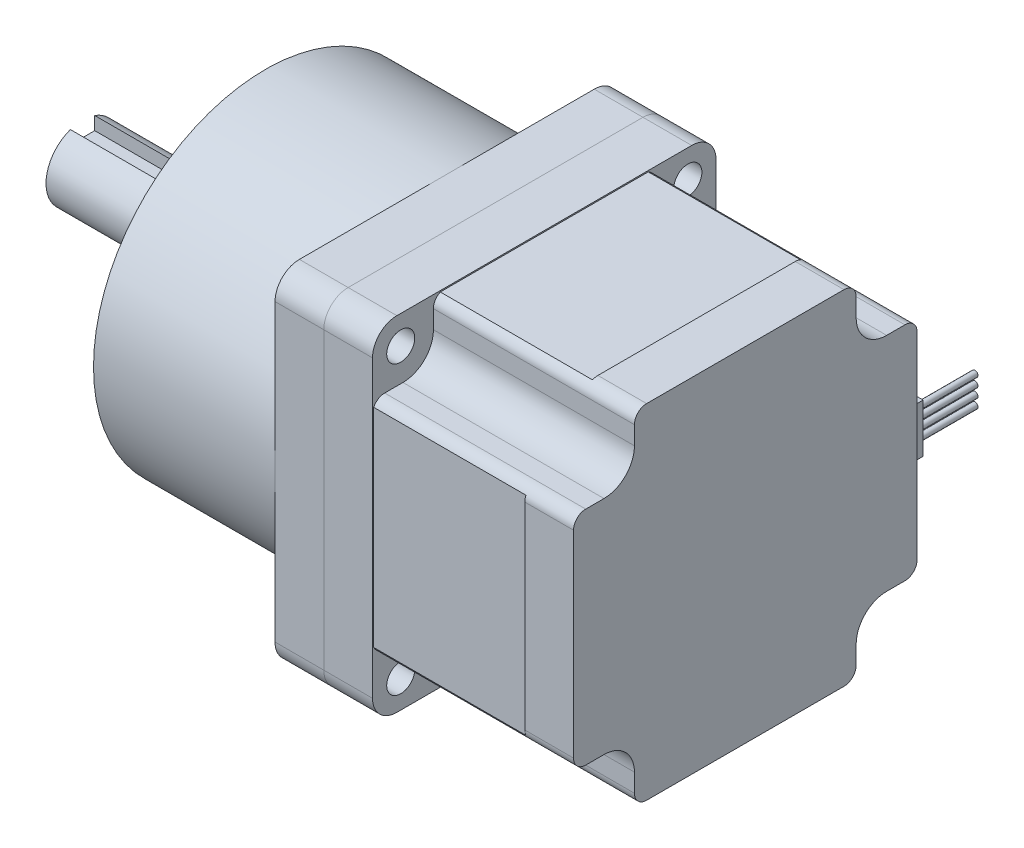
SolidWorks part; units mm, degrees
ref_plane "前视基准面" through (0, 0, 0) normal (0, 0, 1) x (1, 0, 0)
ref_plane "上视基准面" through (0, 0, 0) normal (0, 1, 0) x (1, 0, 0)
ref_plane "右视基准面" through (0, 0, 0) normal (1, 0, 0) x (0, 0, -1)
sketch "草图1" plane through (0, 0, 0) normal (1, 0, 0) x (0, 0, -1)
  line L1 (28.2, -28.2) -> (-28.2, -28.2)
  line L2 (28.2, -28.2) -> (28.2, 28.2)
  line L3 (28.2, 28.2) -> (-28.2, 28.2)
  line L4 (-28.2, -28.2) -> (-28.2, 28.2)
  line L5 (28.2, -28.2) -> (-28.2, 28.2) construction
  line L6 (28.2, 28.2) -> (-28.2, -28.2) construction
  point P0 (0, 0)
  dimension "D1" = 56.4
  dimension "D2" = 56.4
extrude "凸台-拉伸1" add sketch "草图1" along normal mid plane 41
sketch "草图7" plane through (0, 0, 0) normal (1, 0, 0) x (0, 0, -1)
  line L1 (28, 28) -> (-28, 28)
  line L2 (28, 28) -> (28, -28)
  line L3 (28, -28) -> (-28, -28)
  line L4 (-28, 28) -> (-28, -28)
  line L5 (28, 28) -> (-28, -28) construction
  line L6 (28, -28) -> (-28, 28) construction
  line L7 (28.2, -28.2) -> (-28.2, -28.2)
  line L8 (28.2, -28.2) -> (28.2, 28.2)
  line L9 (28.2, 28.2) -> (-28.2, 28.2)
  line L10 (-28.2, -28.2) -> (-28.2, 28.2)
  line L11 (28.2, -28.2) -> (-28.2, 28.2) construction
  line L12 (28.2, 28.2) -> (-28.2, -28.2) construction
  point P0 (0, 0)
  point P6 (0, 0)
  dimension "D1" = 56
  dimension "D2" = 56
  dimension "D3" = 56.4
  dimension "D4" = 56.4
extrude "切除-拉伸1" cut sketch "草图7" against normal mid plane 25
sketch "草图2" plane through (-20.5, 0, 0) normal (-1, 0, 0) x (0, 0, 1)
  circle A0 centre (0, 0) radius 19.05
  dimension "D1" = 38.1
extrude "凸台-拉伸2" add sketch "草图2" along normal blind 1.6
sketch "草图3" plane through (-22.1, 0, 0) normal (-1, 0, 0) x (0, 0, 1)
  circle A0 centre (0, 0) radius 3.175
  dimension "D1" = 6.35
extrude "凸台-拉伸3" add sketch "草图3" along normal blind 19
sketch "草图10" plane through (0, 0, -28.2) normal (0, 0, -1) x (-1, 0, 0)
  line L0 (-20.5, -28.2) -> (-20.5, 28.2) construction
  line L1 (-18.5, -4) -> (-15.5, -4)
  line L2 (-18.5, -4) -> (-18.5, 4)
  line L3 (-18.5, 4) -> (-15.5, 4)
  line L4 (-15.5, -4) -> (-15.5, 4)
  line L5 (-18.5, -4) -> (-15.5, 4) construction
  line L6 (-18.5, 4) -> (-15.5, -4) construction
  point P0 (-17, 0)
  dimension "D1" = 8
  dimension "D2" = 3
  dimension "D3" = 2
  dimension "D4" = 0
extrude "凸台-拉伸4" add sketch "草图10" along normal blind 3
sketch "草图11" plane through (0, 0, -31.2) normal (0, 0, -1) x (-1, 0, 0)
  line L2 (-18.5, -4) -> (-15.5, -4) construction
  line L3 (-18.5, 4) -> (-18.5, -4) construction
  circle A2 centre (-17, -2.5) radius 0.5
  circle A3 centre (-17, -1) radius 0.5
  circle A4 centre (-17, 0.5) radius 0.5
  circle A5 centre (-17, 2) radius 0.5
  point P0 (-17, -4)
  dimension "D2" = 1.5
  dimension "D3" = 1.5
  dimension "D4" = 1
  dimension "D5" = 1
  dimension "D6" = 1
  dimension "D7" = 1
  dimension "D8" = 1.5
  dimension "D9" = 1.5
  dimension "D10" = 1.5
  dimension "D13" = 1.5
  dimension "D14" = 1.5
  dimension "D15" = 1.5
extrude "凸台-拉伸5" add sketch "草图11" along normal blind 10
sketch "草图12" plane through (20.5, 0, 0) normal (1, 0, 0) x (0, 0, -1)
  line L1 (28.2, -28.2) -> (18.2, -28.2)
  line L2 (28.2, -28.2) -> (28.2, -18.2)
  line L3 (28.2, -18.2) -> (18.2, -18.2)
  line L4 (18.2, -28.2) -> (18.2, -18.2)
  line L5 (-28.2, -28.2) -> (-18.2, -28.2)
  line L6 (-28.2, -28.2) -> (-28.2, -18.2)
  line L7 (-28.2, -18.2) -> (-18.2, -18.2)
  line L8 (-18.2, -28.2) -> (-18.2, -18.2)
  line L9 (-28.2, 28.2) -> (-18.2, 28.2)
  line L10 (-28.2, 28.2) -> (-28.2, 18.2)
  line L11 (-28.2, 18.2) -> (-18.2, 18.2)
  line L12 (-18.2, 28.2) -> (-18.2, 18.2)
  line L13 (28.2, 28.2) -> (18.2, 28.2)
  line L14 (28.2, 28.2) -> (28.2, 18.2)
  line L15 (28.2, 18.2) -> (18.2, 18.2)
  line L16 (18.2, 28.2) -> (18.2, 18.2)
  dimension "D1" = 10
  dimension "D2" = 10
  dimension "D3" = 10
  dimension "D4" = 10
  dimension "D5" = 10
  dimension "D6" = 10
  dimension "D7" = 10
  dimension "D8" = 10
extrude "切除-拉伸2" cut sketch "草图12" against normal blind 33
fillet "圆角2" radius 5 4 edges at (4, -18.2, 18.2) (4, 18.2, 18.2) (4, 18.2, -18.2) (4, -18.2, -18.2)
fillet "圆角3" radius 2 8 edges at (16.5, 28.2, -18.2) (16.5, 28.2, 18.2) (16.5, 18.2, 28.2) (16.5, -18.2, 28.2) (16.5, -28.2, 18.2) (16.5, -28.2, -18.2) (16.5, -18.2, -28.2) (16.5, 18.2, -28.2)
hole_wizard "Ø4.6 (4.6) 直径孔1" positions "草图5" profile "草图4" hole size "Ø4.6" standard "Gb"
sketch "草图5" plane through (-20.5, 0, 0) normal (-1, 0, 0) x (0, 0, 1)
  line L0 (38.17, 0) -> (-38.17, 0) construction
  line L1 (0, -31.02) -> (0, 31.02) construction
  point P0 (-23.57, 23.57)
  point P2 (23.57, 23.57)
  point P4 (23.57, -23.57)
  point P6 (-23.57, -23.57)
  dimension "D1" = 47.14
  dimension "D2" = 47.14
  dimension "D3" = 23.57
  dimension "D4" = 23.57
  dimension "D5" = 47.14
  dimension "D6" = 47.14
  dimension "D7" = 23.57
sketch "草图4" plane through (-20.5, 23.57, -23.57) normal (0, 1, 0) x (0, 0, 1)
  line L0 (0, 0) -> (0, 11.382)
  line L1 (0, 11.382) -> (2.3, 10)
  line L2 (2.3, 10) -> (2.3, 0)
  line L5 (2.3, 0) -> (0, 0)
  line L10 (0, 11.382) -> (-2.3, 10) construction
  line L11 (0, -6.35) -> (0, 107.95) construction
  dimension "孔直径" = 4.6
  dimension "孔深度" = 10
  dimension "导头角度" = 118
fillet "圆角1" radius 4 4 edges at (-16.5, -28.2, -28.2) (-16.5, -28.2, 28.2) (-16.5, 28.2, -28.2) (-16.5, 28.2, 28.2)
sketch "草图13" plane through (-20.5, 0, 0) normal (-1, 0, 0) x (0, 0, 1)
  line L4 (-24.2, -28.2) -> (24.2, -28.2)
  line L5 (28.2, -24.2) -> (28.2, 24.2)
  line L6 (24.2, 28.2) -> (-24.2, 28.2)
  line L7 (-28.2, 24.2) -> (-28.2, -24.2)
  line L8 (-24.2, -28.2) -> (24.2, -28.2)
  line L9 (28.2, -24.2) -> (28.2, 24.2)
  line L10 (24.2, 28.2) -> (-24.2, 28.2)
  line L11 (-28.2, 24.2) -> (-28.2, -24.2)
  circle A0 centre (-23.57, 23.57) radius 2.3 construction
  circle A1 centre (23.57, 23.57) radius 2.3 construction
  circle A2 centre (-23.57, -23.57) radius 2.3 construction
  circle A3 centre (23.57, -23.57) radius 2.3 construction
  arc A4 (24.2, -28.2) -> (28.2, -24.2) centre (24.2, -24.2) ccw
  arc A5 (24.2, -28.2) -> (28.2, -24.2) centre (24.2, -24.2) ccw
  arc A6 (28.2, 24.2) -> (24.2, 28.2) centre (24.2, 24.2) ccw
  arc A7 (28.2, 24.2) -> (24.2, 28.2) centre (24.2, 24.2) ccw
  arc A8 (-24.2, 28.2) -> (-28.2, 24.2) centre (-24.2, 24.2) ccw
  arc A9 (-24.2, 28.2) -> (-28.2, 24.2) centre (-24.2, 24.2) ccw
  arc A10 (-28.2, -24.2) -> (-24.2, -28.2) centre (-24.2, -24.2) ccw
  arc A11 (-28.2, -24.2) -> (-24.2, -28.2) centre (-24.2, -24.2) ccw
  circle A12 centre (-23.57, 23.57) radius 2.3
  circle A13 centre (23.57, 23.57) radius 2.3
  circle A14 centre (-23.57, -23.57) radius 2.3
  circle A15 centre (23.57, -23.57) radius 2.3
  dimension "D1" = 0
extrude "凸台-拉伸6" add sketch "草图13" along normal blind 8 separate body
sketch "草图14" plane through (-28.5, 0, 0) normal (-1, 0, 0) x (0, 0, 1)
  circle A0 centre (0, 0) radius 28.2
extrude "凸台-拉伸7" add sketch "草图14" along normal blind 29.8
sketch "草图15" plane through (-58.3, 0, 0) normal (-1, 0, 0) x (0, 0, 1)
  circle A0 centre (0, 0) radius 16
  dimension "D1" = 32
extrude "凸台-拉伸8" add sketch "草图15" along normal blind 2
sketch "草图16" plane through (-60.3, 0, 0) normal (-1, 0, 0) x (0, 0, 1)
  circle A0 centre (0, 0) radius 6
  dimension "D1" = 12
extrude "凸台-拉伸9" add sketch "草图16" along normal blind 28
sketch "草图17" plane through (0, 0, 0) normal (0, 1, 0) x (1, 0, 0)
  line L0 (-88.3, 0) -> (-70.3, 0) construction
  line L1 (-88.3, 6) -> (-88.3, -6) construction
  line L2 (-88.3, 2) -> (-70.3, 2)
  line L3 (-88.3, -2) -> (-70.3, -2)
  arc A0 (-88.3, 2) -> (-88.3, -2) centre (-88.3, 0) ccw
  arc A1 (-70.3, -2) -> (-70.3, 2) centre (-70.3, 0) ccw
  point P5 (-79.3, 0)
  dimension "D2" = 20
  dimension "D1" = 4
extrude "切除-拉伸4" cut sketch "草图17" along normal blind 28 from offset 3.5
sketch "草图18" plane through (-58.3, 0, 0) normal (-1, 0, 0) x (0, 0, 1)
  line L1 (15.9099, -15.9099) -> (-15.9099, -15.9099)
  line L2 (15.9099, -15.9099) -> (15.9099, 15.9099)
  line L3 (15.9099, 15.9099) -> (-15.9099, 15.9099)
  line L4 (-15.9099, -15.9099) -> (-15.9099, 15.9099)
  line L5 (15.9099, -15.9099) -> (-15.9099, 15.9099) construction
  line L6 (15.9099, 15.9099) -> (-15.9099, -15.9099) construction
  point P0 (0, 0)
  dimension "D1" = 45
hole_wizard "M5 螺纹孔1" positions "3D草图1" profile "草图19" tap size "M5" standard "Gb"
sketch3d "3D草图1"
  point P0 (-58.3, 15.9099, -15.9099)
  point P3 (-58.3, 15.9099, 15.9099)
  point P6 (-58.3, -15.9099, -15.9099)
  point P9 (-58.3, -15.9099, 15.9099)
sketch "草图19" plane through (-58.3, 15.9099, -15.9099) normal (0, 1, 0) x (0, 0, 1)
  line L0 (0, 0) -> (0, 13.6618)
  line L1 (0, 13.6618) -> (2.1, 12.4)
  line L2 (2.1, 12.4) -> (2.1, 0)
  line L5 (2.1, 0) -> (0, 0)
  line L10 (0, 13.6618) -> (-2.1, 12.4) construction
  line L11 (0, -6.35) -> (0, 107.95) construction
  dimension "螺纹孔钻头直径" = 4.2
  dimension "螺纹孔钻头深度" = 12.4
  dimension "导头角度" = 118
